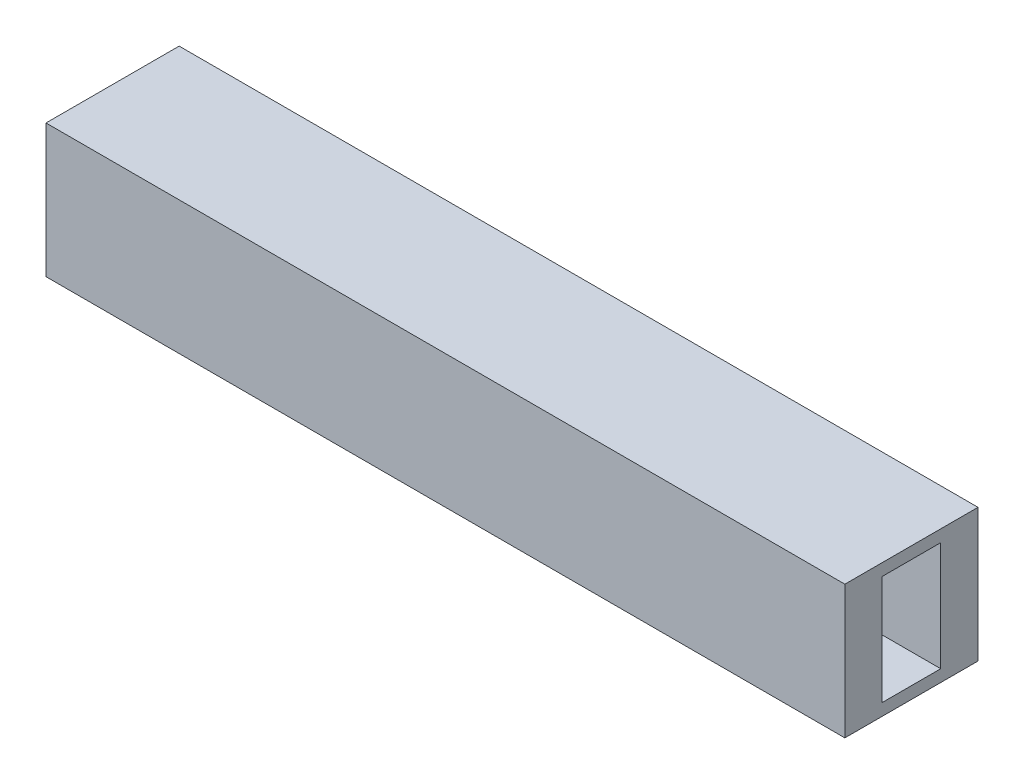
SolidWorks part; units mm, degrees
ref_plane "Front Plane" through (0, 0, 0) normal (0, 0, 1) x (1, 0, 0)
ref_plane "Top Plane" through (0, 0, 0) normal (0, 1, 0) x (1, 0, 0)
ref_plane "Right Plane" through (0, 0, 0) normal (1, 0, 0) x (0, 0, -1)
sketch "Sketch1" plane through (0, 0, 0) normal (1, 0, 0) x (0, 0, -1)
  line L1 (25, -25) -> (-25, -25)
  line L2 (25, -25) -> (25, 25)
  line L3 (25, 25) -> (-25, 25)
  line L4 (-25, -25) -> (-25, 25)
  line L5 (25, -25) -> (-25, 25) construction
  line L6 (25, 25) -> (-25, -25) construction
  point P0 (0, 0)
  dimension "D1" = 50
  dimension "D2" = 50
extrude "Boss-Extrude1" add sketch "Sketch1" along normal blind 300
sketch "Sketch3" plane through (0, 0, 0) normal (-1, 0, 0) x (0, 0, 1)
  line L1 (-11, -20.5) -> (11, -20.5)
  line L2 (-11, -20.5) -> (-11, 20.5)
  line L3 (-11, 20.5) -> (11, 20.5)
  line L4 (11, -20.5) -> (11, 20.5)
  line L5 (-11, -20.5) -> (11, 20.5) construction
  line L6 (-11, 20.5) -> (11, -20.5) construction
  point P0 (0, 0)
  dimension "D1" = 22
  dimension "D2" = 41
extrude "Cut-Extrude2" cut sketch "Sketch3" against normal up to next
